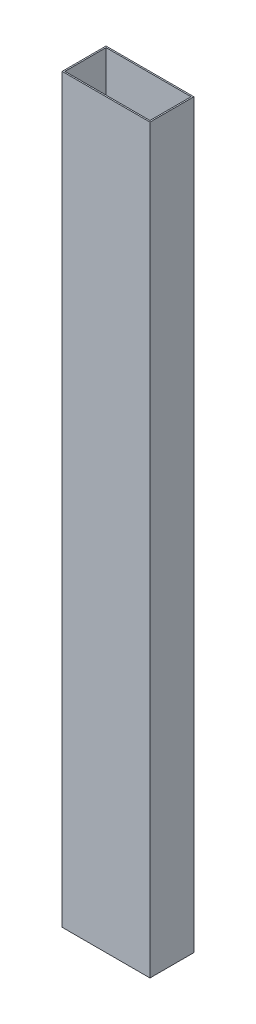
SolidWorks part; units mm, degrees
ref_plane "Front Plane" through (0, 0, 0) normal (0, 0, 1) x (1, 0, 0)
ref_plane "Top Plane" through (0, 0, 0) normal (0, 1, 0) x (1, 0, 0)
ref_plane "Right Plane" through (0, 0, 0) normal (1, 0, 0) x (0, 0, -1)
sketch "Sketch1" plane through (0, 0, 0) normal (0, 1, 0) x (1, 0, 0)
  line L1 (-25.4, -12.7) -> (25.4, -12.7)
  line L2 (-25.4, -12.7) -> (-25.4, 12.7)
  line L3 (-25.4, 12.7) -> (25.4, 12.7)
  line L4 (25.4, -12.7) -> (25.4, 12.7)
  line L5 (-25.4, -12.7) -> (25.4, 12.7) construction
  line L6 (-25.4, 12.7) -> (25.4, -12.7) construction
  point P0 (0, 0)
  dimension "D1" = 50.8
  dimension "D2" = 25.4
extrude "Boss-Extrude1" add sketch "Sketch1" along normal blind 762
sketch "Sketch2" plane through (0, 0, 0) normal (0, -1, 0) x (1, 0, 0)
  line L1 (-24.5999, 11.8999) -> (24.5999, 11.8999)
  line L2 (-24.5999, 11.8999) -> (-24.5999, -11.8999)
  line L3 (-24.5999, -11.8999) -> (24.5999, -11.8999)
  line L4 (24.5999, 11.8999) -> (24.5999, -11.8999)
  line L5 (-24.5999, 11.8999) -> (24.5999, -11.8999) construction
  line L6 (-24.5999, -11.8999) -> (24.5999, 11.8999) construction
  point P0 (0, 0)
  dimension "D1" = 49.1998
  dimension "D2" = 23.7998
extrude "Cut-Extrude1" cut sketch "Sketch2" against normal through all
sketch "Sketch3" plane through (0, 762, 0) normal (0, 1, 0) x (1, 0, 0)
  line L1 (-25.4, 12.7) -> (25.4, 12.7)
  line L2 (-25.4, 12.7) -> (-25.4, -12.7)
  line L3 (-25.4, -12.7) -> (25.4, -12.7)
  line L4 (25.4, 12.7) -> (25.4, -12.7)
extrude "Cut-Extrude2" cut sketch "Sketch3" against normal blind 333.375
